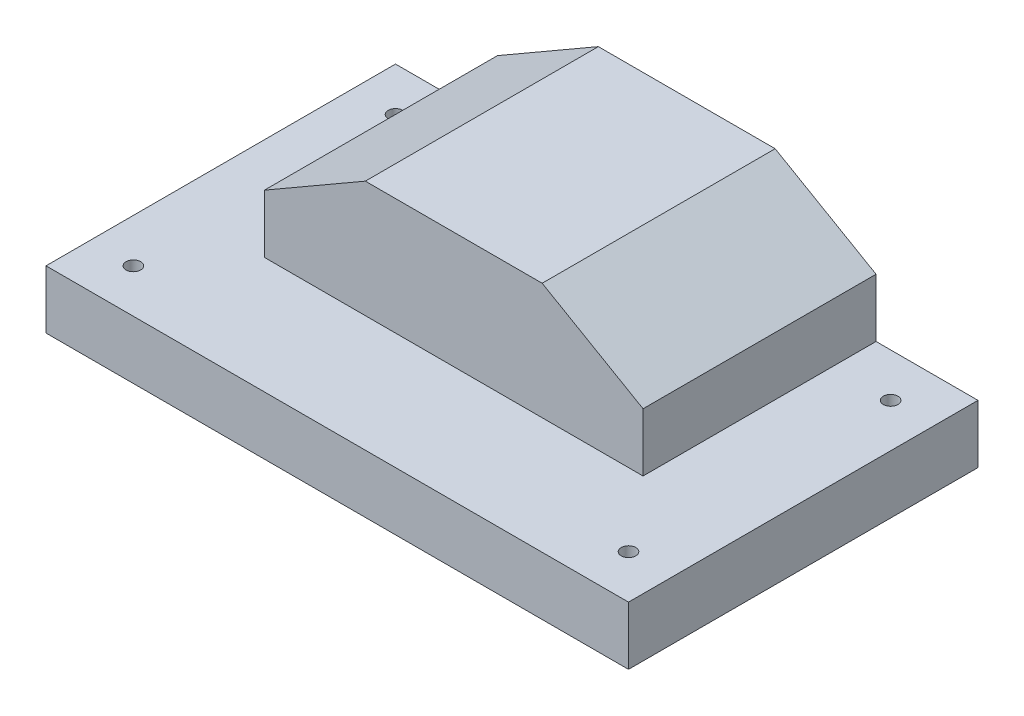
SolidWorks part; units mm, degrees
material "AISI 304"
ref_plane "Front Plane" through (0, 0, 0) normal (0, 0, 1) x (1, 0, 0)
ref_plane "Top Plane" through (0, 0, 0) normal (0, 1, 0) x (1, 0, 0)
ref_plane "Right Plane" through (0, 0, 0) normal (1, 0, 0) x (0, 0, -1)
other "Center of Mass"
sketch "Sketch1" plane through (0, 0, 0) normal (0, 0, 1) x (1, 0, 0)
  line L0 (-63.5, 12.7) -> (-63.5, 0)
  line L1 (-63.5, 0) -> (63.5, 0)
  line L2 (63.5, 0) -> (63.5, 12.7)
  line L3 (63.5, 12.7) -> (-63.5, 12.7)
  point P2 (0, 0)
  dimension "D1" = 12.7
  dimension "D2" = 127
extrude "Boss-Extrude1" add sketch "Sketch1" along normal blind 76.2
sketch "Sketch2" plane through (0, 0, 0) normal (0, 0, -1) x (-1, 0, 0)
  line L0 (0, 0) -> (0, 60.8297) construction
  line L1 (-41.275, 12.7) -> (41.275, 12.7)
  line L2 (-41.275, 12.7) -> (-41.275, 25.4)
  line L3 (-63.5, 12.7) -> (63.5, 12.7) construction
  line L4 (-41.275, 25.4) -> (-19.278, 38.1)
  line L5 (-19.278, 38.1) -> (19.278, 38.1)
  line L6 (19.278, 38.1) -> (41.275, 25.4)
  line L7 (41.275, 25.4) -> (41.275, 12.7)
  point P3 (28.6414, 38.1)
  point P12 (-41.275, 38.1)
  point P13 (-41.275, 38.1)
  point P14 (-29.1044, 38.1)
  dimension "D1" = 82.55
  dimension "D2" = 25.4
  dimension "D3" = 12.7
  dimension "D4" = 30
extrude "Boss-Extrude3" add sketch "Sketch2" against normal blind 50.8
sketch "Sketch4" plane through (0, 12.7, 0) normal (0, 1, 0) x (1, 0, 0)
  line L0 (0, 0) -> (0, -76.2) construction
  line L1 (-53.975, -9.525) -> (53.975, -9.525) construction
  line L2 (-53.975, -9.525) -> (-53.975, -66.675) construction
  line L3 (-53.975, -66.675) -> (53.975, -66.675) construction
  line L4 (53.975, -9.525) -> (53.975, -66.675) construction
  line L5 (63.5, -76.2) -> (-63.5, -76.2) construction
  line L6 (-63.5, -76.2) -> (-63.5, 0) construction
  line L7 (63.5, -76.2) -> (63.5, 0) construction
  line L8 (63.5, 0) -> (41.275, 0) construction
  point P16 (-53.975, -9.525)
  point P17 (-53.975, -66.675)
  point P18 (53.975, -66.675)
  point P19 (53.975, -9.525)
  dimension "D1" = 9.525
  dimension "D2" = 9.525
  dimension "D3" = 9.525
  dimension "D4" = 9.525
hole_wizard "1/8 (0.125) Diameter Hole1" positions "Sketch4" profile "Sketch5" hole size "1/8" standard "ANSI Inch" end condition through all
sketch "Sketch5" plane through (53.975, 12.7, 9.525) normal (1, 0, 0) x (0, 0, 1)
  line L0 (0, 0) -> (0, 12.7)
  line L1 (0, 12.7) -> (1.5875, 12.7)
  line L2 (1.5875, 12.7) -> (1.5875, 0)
  line L5 (1.5875, 0) -> (0, 0)
  line L11 (0, -6.35) -> (0, 107.95) construction
  dimension "Thru Hole Dia." = 3.175
  dimension "Thru Hole Depth" = 12.7
